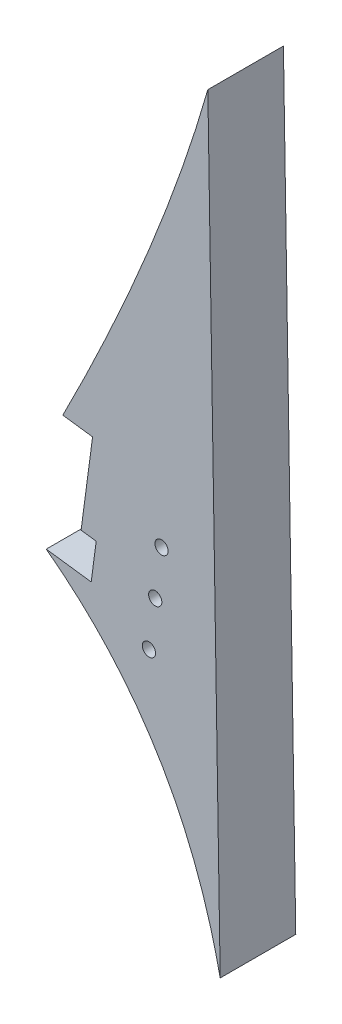
SolidWorks part; units mm, degrees
ref_plane "Front Plane" through (0, 0, 0) normal (0, 0, 1) x (1, 0, 0)
ref_plane "Top Plane" through (0, 0, 0) normal (0, 1, 0) x (1, 0, 0)
ref_plane "Right Plane" through (0, 0, 0) normal (1, 0, 0) x (0, 0, -1)
sketch "Sketch1" plane through (0, 0, 0) normal (0, 0, 1) x (1, 0, 0)
  line L0 (273.4348, -422.9361) -> (270.3947, -445.8352)
  line L1 (270.3947, -445.8352) -> (274.3947, -446.3662)
  line L3 (304.7941, -380.481) -> (306.5276, -487.7615)
  line L6 (273.4348, -422.9361) -> (265.5529, -421.8897)
  line L8 (274.3947, -446.3662) -> (273.0671, -456.3662)
  line L9 (273.0671, -456.3662) -> (261.1715, -454.7869)
  line L10 (306.5276, -487.7615) -> (307.2114, -530.0766)
  line L11 (305.1368, -401.6934) -> (301.8247, -196.7202) construction
  line L13 (304.7941, -380.481) -> (303.9473, -328.0758)
  spline S0 degree 2 poles (261.1715, -454.7869) (296.9639, -481.4674) (307.2114, -530.0766) knots 0 0 0 1 1 1
  spline S1 degree 2 poles (303.9473, -328.0758) (291.9382, -370.1994) (265.5529, -421.8897) knots 0 0 0 1 1 1
  point P7 (290.7566, -328.6299)
  dimension "D1" = 4
  dimension "D2" = 10
  dimension "D3" = 12
  dimension "D4" = 23.1
extrude "Boss-Extrude1" add sketch "Sketch1" along normal blind 20
sketch "Sketch2" plane through (0, 0, 20) normal (0, 0, 1) x (1, 0, 0)
  line L0 (288.3529, -464.1799) -> (291.6804, -439.1158) construction
  line L2 (273.4348, -422.9361) -> (270.3947, -445.8352) construction
  circle A0 centre (288.3529, -464.1799) radius 1.75
  circle A1 centre (290.0167, -451.6478) radius 1.75
  circle A2 centre (291.6804, -439.1158) radius 1.75
  dimension "D1" = 3.5
extrude "Cut-Extrude1" cut sketch "Sketch2" against normal through all
